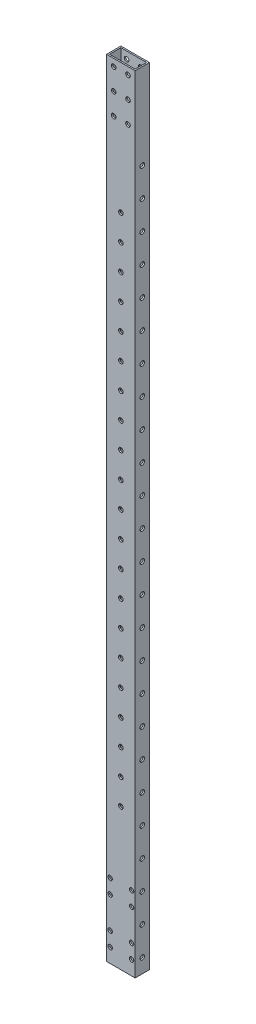
SolidWorks part; units mm, degrees
ref_plane "前视基准面" through (0, 0, 0) normal (0, 0, 1) x (1, 0, 0)
ref_plane "上视基准面" through (0, 0, 0) normal (0, 1, 0) x (1, 0, 0)
ref_plane "右视基准面" through (0, 0, 0) normal (1, 0, 0) x (0, 0, -1)
other "Configuration Table"
sketch "草图1" plane through (0, 0, 0) normal (0, 1, 0) x (1, 0, 0)
  line L1 (-10, -5) -> (10, -5)
  line L2 (-10, -5) -> (-10, 5)
  line L3 (-10, 5) -> (10, 5)
  line L4 (10, -5) -> (10, 5)
  line L5 (-10, -5) -> (10, 5) construction
  line L6 (-10, 5) -> (10, -5) construction
  point P0 (0, 0)
  dimension "D1" = 20
  dimension "D2" = 10
extrude "拉伸-薄壁1" add sketch "草图1" along normal blind 500 thin thin type one direction reverse wall 1
sketch "草图2" plane through (0, 0, -5) normal (0, 0, -1) x (-1, 0, 0)
  line L0 (-10, 500) -> (-10, 0) construction
  line L1 (10, 0) -> (-10, 0) construction
  line L2 (10, 0) -> (10, 30) construction
  line L3 (10, 30) -> (-10, 30) construction
  line L4 (-10, 0) -> (-10, 30) construction
  line L5 (-10, 15) -> (10, 15) construction
  line L6 (0, 0) -> (0, 30) construction
  line L7 (-10, 46.9) -> (10, 46.9) construction
  circle A0 centre (-7.5, 20) radius 1.55
  circle A1 centre (-7.5, 10) radius 1.55
  circle A2 centre (7.5, 10) radius 1.55
  circle A3 centre (7.5, 20) radius 1.55
  circle A4 centre (-7.5, 51.9) radius 1.55
  circle A5 centre (-7.5, 41.9) radius 1.55
  circle A6 centre (7.5, 41.9) radius 1.55
  circle A7 centre (7.5, 51.9) radius 1.55
  dimension "D2" = 3.1
  dimension "D1" = 30
  dimension "D3" = 15
  dimension "D4" = 10
  dimension "D5" = 2
extrude "切除-拉伸1" cut sketch "草图2" against normal through all
sketch "草图3" plane through (-10, 0, 0) normal (-1, 0, 0) x (0, 0, 1)
  line L0 (-5, 0) -> (5, 0) construction
  circle A0 centre (0, 10) radius 1.6
  circle A1 centre (0, 30) radius 1.6
  circle A2 centre (0, 50) radius 1.6
  circle A3 centre (0, 70) radius 1.6
  circle A4 centre (0, 90) radius 1.6
  circle A5 centre (0, 110) radius 1.6
  circle A6 centre (0, 130) radius 1.6
  circle A7 centre (0, 150) radius 1.6
  circle A8 centre (0, 170) radius 1.6
  circle A9 centre (0, 190) radius 1.6
  circle A10 centre (0, 210) radius 1.6
  circle A11 centre (0, 230) radius 1.6
  circle A12 centre (0, 250) radius 1.6
  circle A13 centre (0, 270) radius 1.6
  circle A14 centre (0, 290) radius 1.6
  circle A15 centre (0, 310) radius 1.6
  circle A16 centre (0, 330) radius 1.6
  circle A17 centre (0, 350) radius 1.6
  circle A18 centre (0, 370) radius 1.6
  circle A19 centre (0, 390) radius 1.6
  circle A20 centre (0, 410) radius 1.6
  circle A21 centre (0, 430) radius 1.6
  circle A22 centre (0, 450) radius 1.6
  circle A23 centre (0, 470) radius 1.6
  circle A24 centre (0, 490) radius 1.6
  dimension "D1" = 3.2
  dimension "D2" = 10
  dimension "D3" = 25
extrude "切除-拉伸2" cut sketch "草图3" against normal through all
sketch "草图4" plane through (0, 500, 0) normal (0, 1, 0) x (1, 0, 0)
  line L1 (-10, 5) -> (10, 5)
  line L2 (-10, 5) -> (-10, -5)
  line L3 (-10, -5) -> (10, -5)
  line L4 (10, 5) -> (10, -5)
extrude "拉伸-薄壁2" add sketch "草图4" along normal blind 50 thin
sketch "草图5" plane through (0, 0, -5) normal (0, 0, -1) x (-1, 0, 0)
  line L0 (10, 550) -> (10, 0) construction
  line L1 (-10, 550) -> (10, 550) construction
  line L2 (-10, 550) -> (-10, 500) construction
  line L3 (-10, 500) -> (10, 500) construction
  line L4 (10, 550) -> (10, 500) construction
  line L5 (-10, 530) -> (10, 530) construction
  line L6 (-10, 550) -> (10, 550) construction
  line L7 (-10, 550) -> (-10, 510) construction
  line L8 (-10, 510) -> (10, 510) construction
  line L9 (10, 550) -> (10, 510) construction
  line L10 (0, 550) -> (0, 510) construction
  line L11 (-5, 545) -> (-5, 530) construction
  line L12 (-5, 530) -> (-5, 515) construction
  line L13 (5, 530) -> (5, 515) construction
  line L14 (5, 545) -> (5, 530) construction
  line L15 (10, 550) -> (10, 510) construction
  circle A0 centre (-5, 530) radius 1.6
  circle A1 centre (-5, 545) radius 1.6
  circle A2 centre (-5, 515) radius 1.6
  circle A3 centre (5, 515) radius 1.6
  circle A4 centre (5, 545) radius 1.6
  circle A5 centre (5, 530) radius 1.6
  dimension "D4" = 3.2
  dimension "D1" = 50
  dimension "D2" = 40
  dimension "D3" = 20
  dimension "D5" = 15
  dimension "D6" = 15
  dimension "D7" = 5
extrude "切除-拉伸3" cut sketch "草图5" against normal through all
sketch "草图6" plane through (0, 0, -5) normal (0, 0, -1) x (-1, 0, 0)
  line L0 (10, 275) -> (-10, 275) construction
  line L1 (10, 550) -> (10, 0) construction
  line L2 (-10, 550) -> (-10, 0) construction
  line L3 (0, 275) -> (0, 294.634) construction
  circle A0 centre (0.0161, 279) radius 1.6
  circle A1 centre (0, 297) radius 1.6
  circle A2 centre (0, 261) radius 1.6
  circle A3 centre (0, 243) radius 1.6
  circle A4 centre (0, 225) radius 1.6
  circle A5 centre (0, 207) radius 1.6
  circle A6 centre (0, 189) radius 1.6
  circle A7 centre (0, 171) radius 1.6
  circle A8 centre (0, 153) radius 1.6
  circle A9 centre (0, 135) radius 1.6
  circle A10 centre (0, 117) radius 1.6
  circle A11 centre (0, 99) radius 1.6
  circle A12 centre (0, 315) radius 1.6
  circle A13 centre (0, 333) radius 1.6
  circle A14 centre (0, 351) radius 1.6
  circle A15 centre (0, 369) radius 1.6
  circle A16 centre (0, 387) radius 1.6
  circle A17 centre (0, 405) radius 1.6
  circle A18 centre (0, 423) radius 1.6
  circle A19 centre (0, 441) radius 1.6
  circle A20 centre (0, 459) radius 1.6
  dimension "D1" = 3.2
  dimension "D2" = 3.2
  dimension "D3" = 3.2
  dimension "D4" = 18
  dimension "D5" = 18
  dimension "D6" = 4
  dimension "D7" = 10
  dimension "D8" = 10
extrude "切除-拉伸4" cut sketch "草图6" against normal through all
